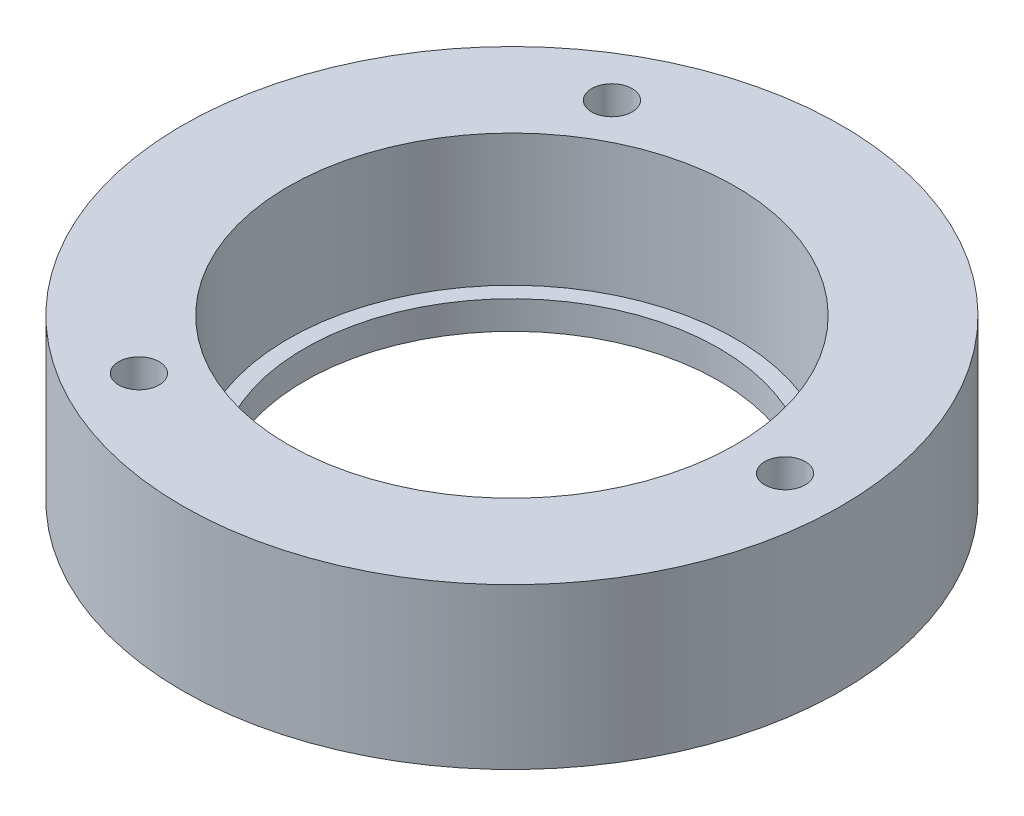
SolidWorks part; units mm, degrees
material "ABS"
ref_plane "前视基准面" through (0, 0, 0) normal (0, 0, 1) x (1, 0, 0)
ref_plane "上视基准面" through (0, 0, 0) normal (0, 1, 0) x (1, 0, 0)
ref_plane "右视基准面" through (0, 0, 0) normal (1, 0, 0) x (0, 0, -1)
sketch "草图1" plane through (0, 0, 0) normal (0, 1, 0) x (1, 0, 0)
  circle A0 centre (0, 0) radius 35
  circle A1 centre (0, 0) radius 22
  dimension "D1" = 70
  dimension "D2" = 44
extrude "凸台-拉伸1" add sketch "草图1" along normal blind 3
sketch "草图2" plane through (0, 3, 0) normal (0, 1, 0) x (1, 0, 0)
  circle A0 centre (0, 0) radius 23.75
  circle A1 centre (0, 0) radius 35
  circle A2 centre (0, 0) radius 35 construction
  dimension "D1" = 47.5
extrude "凸台-拉伸2" add sketch "草图2" along normal blind 14
sketch "草图4" plane through (0, 0, 0) normal (0, 1, 0) x (1, 0, 0)
  line L0 (-35, 0) -> (35, 0) construction
  line L1 (0, 35) -> (0, -35) construction
  circle A0 centre (0, 0) radius 29 construction
  circle A1 centre (0, 0) radius 35 construction
  circle A2 centre (29, 0) radius 2.15
  circle A3 centre (-14.5, -25.1147) radius 2.15
  circle A4 centre (-14.5, 25.1147) radius 2.15
  dimension "D1" = 58
  dimension "D2" = 4.3
  dimension "D3" = 3
extrude "切除-拉伸1" cut sketch "草图4" along normal blind 70
fillet "圆角1" radius 2 3 edges at (-14.5, 0, 27.2647) (-14.5, 0, -22.9647) (29, 0, 2.15)
